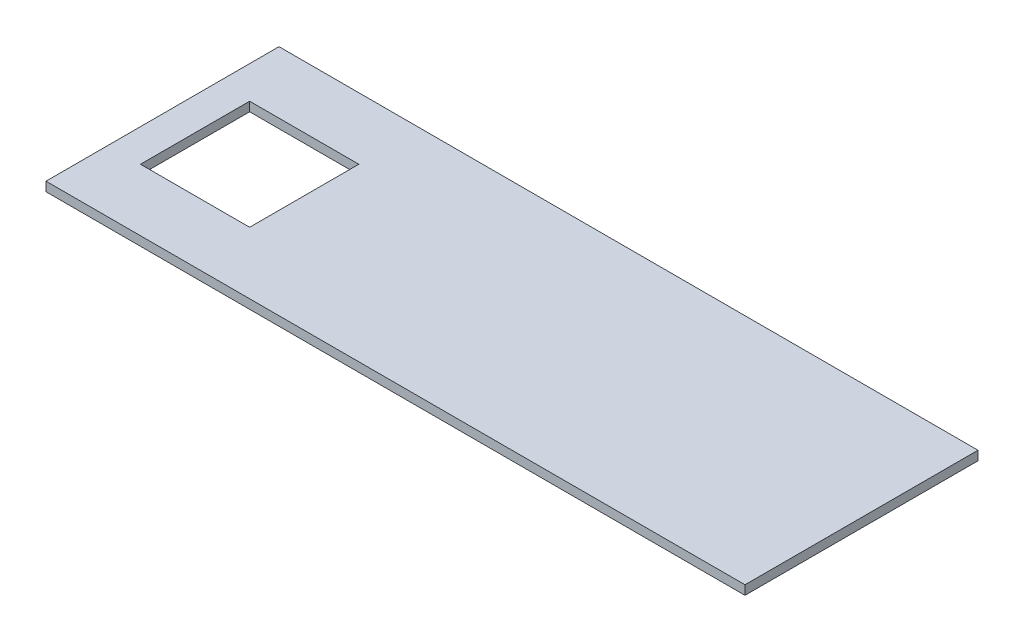
SolidWorks part; units mm, degrees
ref_plane "前视基准面" through (0, 0, 0) normal (0, 0, 1) x (1, 0, 0)
ref_plane "上视基准面" through (0, 0, 0) normal (0, 1, 0) x (1, 0, 0)
ref_plane "右视基准面" through (0, 0, 0) normal (1, 0, 0) x (0, 0, -1)
sketch "草图1" plane through (0, 0, 0) normal (0, 1, 0) x (1, 0, 0)
  line L0 (0, 0) -> (76.2, 0)
  line L1 (0, 0) -> (0, -25.4)
  line L2 (0, -25.4) -> (76.2, -25.4)
  line L3 (76.2, -25.4) -> (76.2, 0)
extrude "凸台-拉伸1" add sketch "草图1" along normal blind 1
sketch "草图2" plane through (0, 1, 0) normal (0, 1, 0) x (1, 0, 0)
  line L2 (3.55, -12.7) -> (3.55, -6.75)
  line L3 (3.55, -6.75) -> (15.45, -6.75)
  line L4 (15.45, -6.75) -> (15.45, -18.65)
  line L5 (15.45, -18.65) -> (3.55, -18.65)
  line L6 (3.55, -18.65) -> (3.55, -12.7)
extrude "切除-拉伸1" cut sketch "草图2" against normal blind 1
